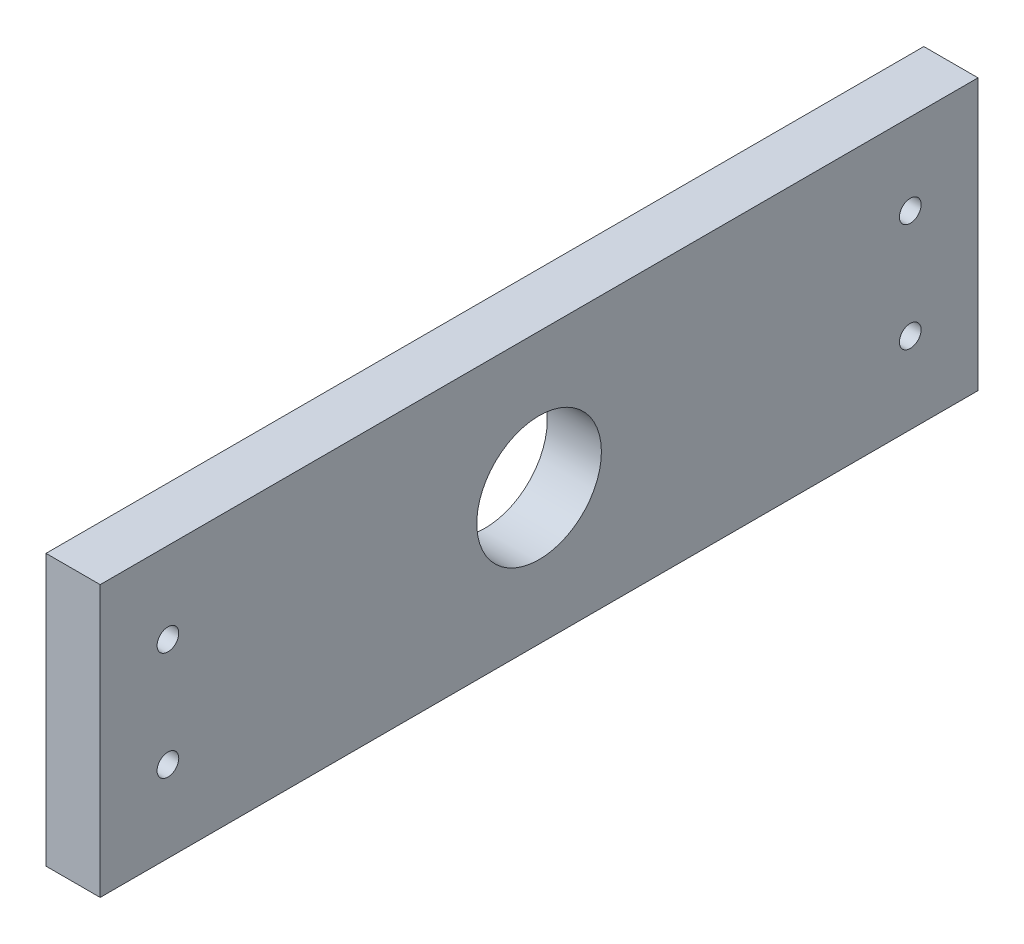
SolidWorks part; units mm, degrees
material "Cedar"
ref_plane "Front Plane" through (0, 0, 0) normal (0, 0, 1) x (1, 0, 0)
ref_plane "Top Plane" through (0, 0, 0) normal (0, 1, 0) x (1, 0, 0)
ref_plane "Right Plane" through (0, 0, 0) normal (1, 0, 0) x (0, 0, -1)
sketch "Sketch1" plane through (0, 0, 0) normal (1, 0, 0) x (0, 0, -1)
  line L0 (0, 0) -> (0, -25) construction
  line L1 (-56, -25) -> (56, -25)
  line L2 (-56, -25) -> (-56, 25)
  line L3 (-56, 25) -> (56, 25)
  line L4 (56, -25) -> (56, 25)
  line L5 (-56, -25) -> (56, 25) construction
  line L6 (-56, 25) -> (56, -25) construction
  line L7 (56, -25) -> (81, -25)
  line L8 (56, -25) -> (56, 25)
  line L9 (56, 25) -> (81, 25)
  line L10 (81, -25) -> (81, 25)
  line L11 (56, -25) -> (81, 25) construction
  line L12 (56, 25) -> (81, -25) construction
  line L13 (56, 0) -> (77, 0) construction
  line L14 (-56, 25) -> (-81, 25)
  line L15 (-81, -25) -> (-81, 25)
  line L16 (-56, -25) -> (-81, -25)
  line L17 (-56, -25) -> (-56, 25)
  circle A7 centre (0, 0) radius 11.5
  circle A8 centre (68.5, 10) radius 2
  circle A9 centre (68.5, -10) radius 2
  circle A10 centre (-68.5, 10) radius 2
  circle A11 centre (-68.5, -10) radius 2
  point P0 (0, 0)
  point P5 (68.5, 0)
  dimension "D7" = 4
  dimension "D8" = 10
  dimension "D9" = 12.5
  dimension "D10" = 23
  dimension "D1" = 112
  dimension "D2" = 50
  dimension "D3" = 25
  dimension "D4" = 50
  dimension "D5" = 12.5
  dimension "D6" = 25
extrude "Boss-Extrude1" add sketch "Sketch1" along normal blind 10
